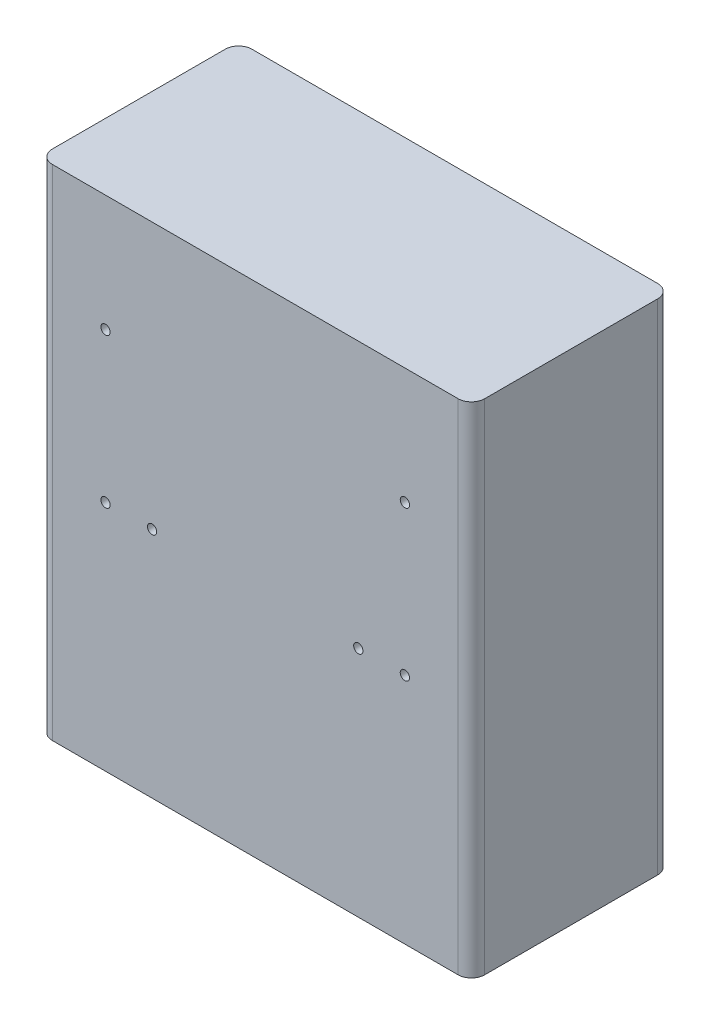
SolidWorks part; units mm, degrees
material "Mahogany"
ref_plane "Front Plane" through (0, 0, 0) normal (0, 0, 1) x (1, 0, 0)
ref_plane "Top Plane" through (0, 0, 0) normal (0, 1, 0) x (1, 0, 0)
ref_plane "Right Plane" through (0, 0, 0) normal (1, 0, 0) x (0, 0, -1)
sketch "Sketch1" plane through (0, 0, 0) normal (0, 0, 1) x (1, 0, 0)
  line L1 (-41.275, -47.625) -> (41.275, -47.625)
  line L2 (-41.275, -47.625) -> (-41.275, 47.625)
  line L3 (-41.275, 47.625) -> (41.275, 47.625)
  line L4 (41.275, -47.625) -> (41.275, 47.625)
  line L5 (-41.275, -47.625) -> (41.275, 47.625) construction
  line L6 (-41.275, 47.625) -> (41.275, -47.625) construction
  point P0 (0, 0)
  dimension "D1" = 82.55
  dimension "D2" = 95.25
extrude "Boss-Extrude1" add sketch "Sketch1" along normal mid plane 38.1
sketch "Sketch2" plane through (0, 0, 19.05) normal (0, 0, 1) x (1, 0, 0)
  line L0 (41.275, -47.625) -> (41.275, 47.625) construction
  line L1 (-28.575, -3.175) -> (28.575, -3.175) construction
  line L2 (-28.575, -3.175) -> (-28.575, 25.4) construction
  line L3 (-28.575, 25.4) -> (28.575, 25.4) construction
  line L4 (28.575, -3.175) -> (28.575, 25.4) construction
  line L5 (-28.575, -3.175) -> (28.575, 25.4) construction
  line L6 (-28.575, 25.4) -> (28.575, -3.175) construction
  line L7 (41.275, 47.625) -> (-41.275, 47.625) construction
  circle A0 centre (-28.575, 25.4) radius 0.889
  circle A1 centre (28.575, 25.4) radius 0.889
  circle A2 centre (28.575, -3.175) radius 0.889
  circle A3 centre (-28.575, -3.175) radius 0.889
  circle A4 centre (-19.685, -3.175) radius 0.889
  circle A5 centre (19.685, -3.175) radius 0.889
  point P10 (0, 11.1125)
  dimension "D1" = 1.778
  dimension "D2" = 12.7
  dimension "D3" = 22.225
  dimension "D4" = 50.8
  dimension "D5" = 8.89
  dimension "D6" = 8.89
extrude "Cut-Extrude1" cut sketch "Sketch2" against normal through all
fillet "Fillet1" radius 2.54 4 edges at (-41.275, 0, -19.05) (41.275, 0, -19.05) (41.275, 0, 19.05) (-41.275, 0, 19.05)
